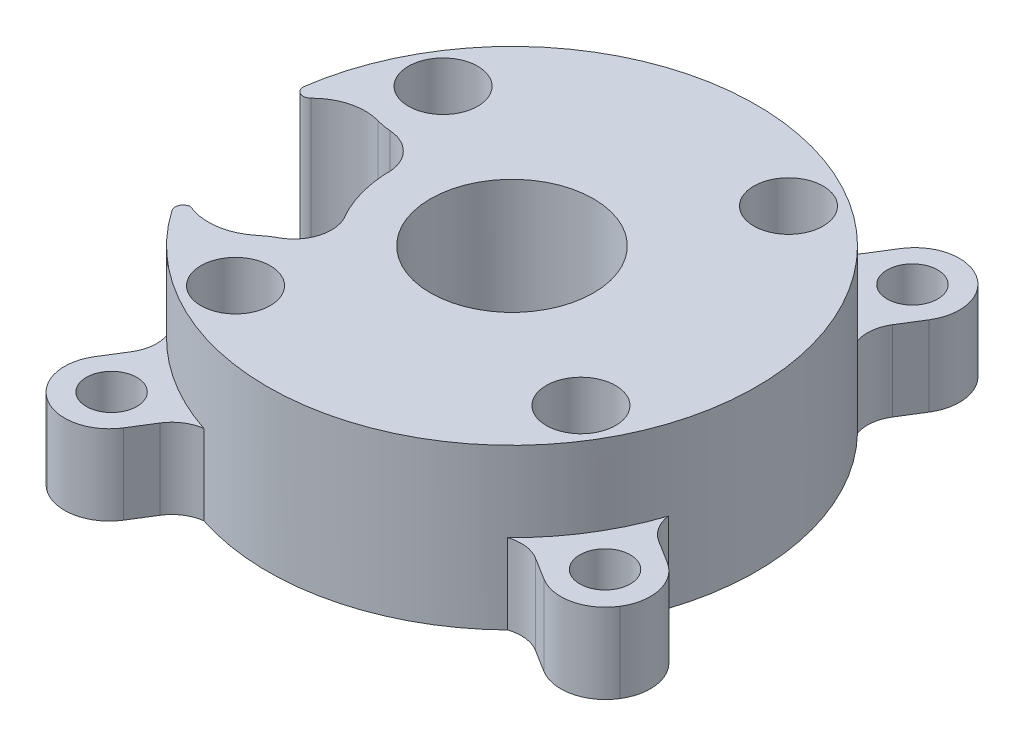
SolidWorks part; units mm, degrees
ref_plane "Front Plane" through (0, 0, 0) normal (0, 0, 1) x (1, 0, 0)
ref_plane "Top Plane" through (0, 0, 0) normal (0, 1, 0) x (1, 0, 0)
ref_plane "Right Plane" through (0, 0, 0) normal (1, 0, 0) x (0, 0, -1)
sketch "Sketch1" plane through (0, 0, 0) normal (0, 1, 0) x (1, 0, 0)
  line L0 (-7.8696, -16.5329) -> (-4.3445, -17.9784) construction
  line L2 (-5.1285, -8.2334) -> (-7.1429, -11.4673) construction
  line L3 (-5.1285, -8.2334) -> (0, 0) construction
  line L4 (-4.4173, -15.8896) -> (-5.3876, -15.4917)
  line L5 (-6.8331, -19.0168) -> (-5.8628, -19.4147)
  line L6 (-10.7934, 4.6284) -> (-9.9033, 4.0739)
  line L22 (-8.9133, 7.6467) -> (-8.0232, 7.0923)
  line L25 (-4.6284, -10.7934) -> (-4.0739, -9.9033)
  line L26 (-7.6467, -8.9133) -> (-7.0923, -8.0232)
  line L33 (-8.2334, 5.1285) -> (-11.4673, 7.1429) construction
  line L34 (4.6284, 10.7934) -> (4.0739, 9.9033)
  line L35 (7.6467, 8.9133) -> (7.0923, 8.0232)
  line L36 (5.1285, 8.2334) -> (7.1429, 11.4673) construction
  line L37 (10.7934, -4.6284) -> (9.9033, -4.0739)
  line L38 (8.9133, -7.6467) -> (8.0232, -7.0923)
  line L39 (8.2334, -5.1285) -> (11.4673, -7.1429) construction
  arc A2 (-3.014, -9.2199) -> (-6.9463, -6.7705) centre (0, 0) ccw
  arc A3 (-9.9033, 4.0739) -> (-9.2199, 3.014) centre (-10.6843, 2.8201) cw
  arc A4 (-11.3595, 7.0757) -> (-10.7934, 4.6284) centre (-9.8553, 6.1345) ccw
  arc A6 (-11.3595, 7.0757) -> (-8.9133, 7.6467) centre (-9.8515, 6.1406) cw
  arc A42 (-4.4173, -15.8896) -> (-2.8621, -15.4979) centre (-3.905, -14.6404) ccw
  arc A43 (-5.3876, -15.4917) -> (-7.8696, -16.5329) centre (-6.109, -17.251) ccw
  arc A45 (-7.8696, -16.5329) -> (-6.8331, -19.0168) centre (-6.1117, -17.2576) ccw
  arc A46 (-5.0304, -20.7855) -> (-5.8628, -19.4147) centre (-6.375, -20.664) ccw
  arc A47 (-2.8621, -15.4979) -> (-5.0304, -20.7855) centre (4.6303, -21.6586) ccw
  arc A48 (-8.0232, 7.0923) -> (-6.7705, 6.9463) centre (-7.2422, 8.3461) ccw
  arc A49 (-4.0739, -9.9033) -> (-3.014, -9.2199) centre (-2.8201, -10.6843) cw
  arc A50 (-7.0757, -11.3595) -> (-4.6284, -10.7934) centre (-6.1345, -9.8553) ccw
  arc A51 (-7.0757, -11.3595) -> (-7.6467, -8.9133) centre (-6.1406, -9.8515) cw
  arc A52 (-7.0923, -8.0232) -> (-6.9463, -6.7705) centre (-8.3461, -7.2422) ccw
  arc A53 (4.0739, 9.9033) -> (3.014, 9.2199) centre (2.8201, 10.6843) cw
  arc A54 (7.0757, 11.3595) -> (4.6284, 10.7934) centre (6.1345, 9.8553) ccw
  arc A55 (7.0757, 11.3595) -> (7.6467, 8.9133) centre (6.1406, 9.8515) cw
  arc A56 (7.0923, 8.0232) -> (6.9463, 6.7705) centre (8.3461, 7.2422) ccw
  arc A57 (9.9033, -4.0739) -> (9.2199, -3.014) centre (10.6843, -2.8201) cw
  arc A58 (11.3595, -7.0757) -> (10.7934, -4.6284) centre (9.8553, -6.1345) ccw
  arc A59 (11.3595, -7.0757) -> (8.9133, -7.6467) centre (9.8515, -6.1406) cw
  arc A60 (8.0232, -7.0923) -> (6.7705, -6.9463) centre (7.2422, -8.3461) ccw
  point P42 (-13.0295, 5.5229)
  point P43 (-11.993, 3.0389)
  point P44 (-11.2689, 4.8048)
  point P45 (-11.2716, 4.7982)
  point P46 (-11.0227, 2.6411)
  point P47 (-10.5475, 6.5641)
  point P48 (-11.5349, 1.3918)
  point P49 (-10.1902, 1.2703)
  point P53 (-2.4431, -9.256)
  point P56 (-10.2156, 2.0562)
  point P57 (-0.5296, 0.3972)
  point P58 (-8.5918, 6.0161)
  point P64 (-7.2304, -6.274)
  point P102 (0, 0)
  dimension "D9" = 1.9014
  dimension "D11" = 1.3502
  dimension "D13" = 1.905
  dimension "D3" = 3.81
  dimension "D10" = 1.0487
extrude "Boss-Extrude2" add sketch "Sketch1" along normal blind 3.175 contours A48 L22 A6 A4 L6 A3 A2 | A52 L26 A51 A50 L25 A49 A2 | A56 L35 A55 A54 L34 A53 A2 | A60 L38 A59 A58 L37 A57 A2
sketch "Sketch3" plane through (0, 3.175, 0) normal (0, 1, 0) x (1, 0, 0)
  circle A0 centre (0, 0) radius 9.7
extrude "Boss-Extrude4" add sketch "Sketch3" along normal blind 3.175
sketch "Sketch4" plane through (0, 3.175, 0) normal (0, 1, 0) x (1, 0, 0)
  line L0 (-7.0757, -11.3595) -> (-5.1285, -8.2334) construction
  arc A0 (-6.9463, -6.7705) -> (-3.014, -9.2199) centre (0, 0) ccw construction
  circle A1 centre (-6.1021, -9.7965) radius 1.0033
  circle A2 centre (-9.7965, 6.1021) radius 1.0033
  circle A3 centre (6.1021, 9.7965) radius 1.0033
  circle A4 centre (9.7965, -6.1021) radius 1.0033
  dimension "D1" = 2.0066
  dimension "D3" = 9.7965
  dimension "D4" = 11.5415
  dimension "D2" = 4
extrude "Cut-Extrude1" cut sketch "Sketch4" against normal blind 3.175
sketch "Sketch6" plane through (0, 0, 0) normal (0, -1, 0) x (1, 0, 0)
  line L0 (-8.6009, 2.0015) -> (-4.7665, 1.2946) construction
  circle A0 centre (0, 0) radius 9.7 construction
  circle A1 centre (-4.1203, 6.8573) radius 1.25
  arc A2 (-7.7408, 4.1889) -> (-8.8653, -0.334) centre (0.1332, -0.17) ccw
  arc A3 (-8.8653, -0.334) -> (-6.9609, -1.6427) centre (-7.3713, -0.1999) ccw
  arc A4 (-6.3873, -1.5416) -> (-4.9858, 0.0725) centre (-6.4812, -0.0445) ccw
  arc A5 (-5.4387, 4.7136) -> (-7.7408, 4.1889) centre (-6.3841, 3.5491) ccw
  arc A6 (-4.2583, 2.4276) -> (-4.9451, 4.3741) centre (-5.6282, 3.0387) ccw
  arc A7 (-4.2583, 2.4276) -> (-4.9858, 0.0725) centre (0.1064, -0.2106) ccw
  circle A8 centre (6.8573, 4.1203) radius 1.25
  circle A9 centre (4.1203, -6.8573) radius 1.25
  circle A10 centre (-6.8573, -4.1203) radius 1.25
  parabola Q0 (-6.9609, -1.6427) -> (-6.3873, -1.5416) focus (-6.003, -2.6403) apex (-5.7771, -1.5853)
  spline S0 degree 2 poles (-4.9451, 4.3741) (-5.0821, 4.4442) (-5.2471, 4.5653) (-5.34, 4.6335) (-5.4387, 4.7136) knots 0 0 0 0.6 0.6 1 1 1
  point P29 (0, 0)
  dimension "D2" = 1.5
extrude "Cut-Extrude2" cut sketch "Sketch6" against normal through all
sketch "Sketch7" plane through (0, 0, 0) normal (0, -1, 0) x (1, 0, 0)
  arc A0 (-6.9463, 6.7705) -> (-9.2199, -3.014) centre (0, 0) ccw construction
  arc A2 (-6.9609, -1.6427) -> (-9.6852, 0.5356) centre (-7.5467, 0.4174) cw
  arc A4 (-5.4387, 4.7136) -> (-8.8941, 3.871) centre (-6.8464, 2.9798) ccw
  arc A6 (-6.9463, 6.7705) -> (-9.2199, -3.014) centre (0, 0) ccw
  arc A7 (-8.8941, 3.871) -> (-9.6852, 0.5356) centre (0, 0) ccw
  arc A16 (-8.8653, -0.334) -> (-6.9609, -1.6427) centre (-7.3713, -0.1999) ccw
  arc A17 (-7.7408, 4.1889) -> (-8.8653, -0.334) centre (0.1332, -0.17) ccw
  arc A18 (-5.4387, 4.7136) -> (-7.7408, 4.1889) centre (-6.3841, 3.5491) ccw
  arc A19 (-8.8653, -0.334) -> (-6.9609, -1.6427) centre (-7.3713, -0.1999) ccw
  arc A20 (-7.7408, 4.1889) -> (-8.8653, -0.334) centre (0.1332, -0.17) ccw
  arc A21 (-5.4387, 4.7136) -> (-7.7408, 4.1889) centre (-6.3841, 3.5491) ccw
  parabola Q23 (-6.9609, -1.6427) -> (-6.3873, -1.5416) focus (-6.003, -2.6403) apex (-5.7771, -1.5853) construction
  spline S0 degree 2 poles (-4.9451, 4.3741) (-5.0821, 4.4442) (-5.2471, 4.5653) (-5.34, 4.6335) (-5.4387, 4.7136) knots 0 0 0 0.6 0.6 1 1 1 construction
  dimension "D1" = 0
  dimension "D2" = 0
extrude "Cut-Extrude3" cut sketch "Sketch7" against normal through all
sketch "Sketch8" plane through (0, 0, 0) normal (0, -1, 0) x (1, 0, 0)
  line L0 (0, 0) -> (-4.7665, 1.2946) construction
  line L1 (-9.6043, -1.3592) -> (-10.3645, 0.8697)
  line L2 (-10.3645, 0.8697) -> (-8.848, 0.8697)
  line L3 (-8.848, 0.8697) -> (-9.0664, -1.0918)
  line L4 (-8.8941, 3.871) -> (-9.6852, 0.5356) construction
  line L5 (-9.2897, 2.2033) -> (0, 0) construction
  line L6 (-8.2961, 3.1965) -> (-7.6103, 5.0472)
  line L7 (-9.6511, 3.8776) -> (-8.2961, 3.1965)
  line L8 (-7.9709, 5.5277) -> (-9.6511, 3.8776)
  arc A0 (-9.6043, -1.3592) -> (-9.0664, -1.0918) centre (-9.291, -1.3148) cw
  arc A1 (-9.6852, 0.5356) -> (-9.2199, -3.014) centre (0, 0) ccw construction
  arc A2 (-9.6852, 0.5356) -> (-6.9613, -1.6428) centre (-7.5467, 0.4174) ccw construction
  arc A3 (-4.2583, 2.4276) -> (-4.9858, 0.0725) centre (0.1064, -0.2106) ccw construction
  arc A4 (-7.9709, 5.5277) -> (-7.6103, 5.0472) centre (-7.7108, 5.3473) ccw
extrude "Cut-Extrude4" cut sketch "Sketch8" against normal through all
sketch "Sketch9" plane through (0, 0, 0) normal (0, -1, 0) x (1, 0, 0)
  circle A0 centre (0, 0) radius 3.2385
  dimension "D1" = 6.477
extrude "Cut-Extrude5" cut sketch "Sketch9" against normal through all
sketch "Sketch11" plane through (0, 6.35, 0) normal (0, 1, 0) x (1, 0, 0)
  circle A0 centre (4.1203, 6.8573) radius 1.25 construction
  circle A1 centre (6.8573, -4.1203) radius 1.25 construction
  circle A2 centre (-4.1203, -6.8573) radius 1.25 construction
  circle A3 centre (-6.8573, 4.1203) radius 1.25 construction
  circle A4 centre (4.1203, 6.8573) radius 1.25 construction
  circle A5 centre (6.8573, -4.1203) radius 1.25 construction
  circle A6 centre (-4.1203, -6.8573) radius 1.25 construction
  circle A7 centre (-6.8573, 4.1203) radius 1.25 construction
  circle A8 centre (-6.8573, 4.1203) radius 1.377
  circle A9 centre (4.1203, 6.8573) radius 1.377
  circle A10 centre (6.8573, -4.1203) radius 1.377
  circle A11 centre (-4.1203, -6.8573) radius 1.377
  arc A12 (-7.7287, -5.0314) -> (-7.9709, -5.5277) centre (-7.7108, -5.3473) ccw construction
  arc A13 (-7.7287, -5.0314) -> (-5.4387, -4.7136) centre (-6.8464, -2.9798) ccw construction
  arc A14 (-4.9451, -4.3741) -> (-4.2583, -2.4276) centre (-5.6282, -3.0387) ccw construction
  arc A15 (-4.9858, -0.0725) -> (-4.2583, -2.4276) centre (0.1064, 0.2106) ccw construction
  arc A16 (-9.6043, 1.3592) -> (-9.0664, 1.0918) centre (-9.291, 1.3148) ccw construction
  arc A17 (-6.9613, 1.6428) -> (-9.0664, 1.0918) centre (-7.5467, -0.4174) ccw construction
  arc A18 (-4.9858, -0.0725) -> (-6.3873, 1.5416) centre (-6.4812, 0.0445) ccw construction
  arc A19 (-7.7287, -5.0314) -> (-7.9709, -5.5277) centre (-7.7108, -5.3473) ccw construction
  arc A20 (-7.7287, -5.0314) -> (-5.4387, -4.7136) centre (-6.8464, -2.9798) ccw construction
  arc A21 (-4.9451, -4.3741) -> (-4.2583, -2.4276) centre (-5.6282, -3.0387) ccw construction
  arc A22 (-4.9858, -0.0725) -> (-4.2583, -2.4276) centre (0.1064, 0.2106) ccw construction
  arc A23 (-9.6043, 1.3592) -> (-9.0664, 1.0918) centre (-9.291, 1.3148) ccw construction
  arc A24 (-6.9613, 1.6428) -> (-9.0664, 1.0918) centre (-7.5467, -0.4174) ccw construction
  arc A25 (-4.9858, -0.0725) -> (-6.3873, 1.5416) centre (-6.4812, 0.0445) ccw construction
  parabola Q0 (-6.9609, 1.6427) -> (-6.3873, 1.5416) focus (-6.003, 2.6403) apex (-5.7771, 1.5853) construction
  parabola Q1 (-6.9609, 1.6427) -> (-6.3873, 1.5416) focus (-6.003, 2.6403) apex (-5.7771, 1.5853) construction
  spline S0 degree 2 poles (-1414.679, -2652.3554) (32.7402, 23.3103) (-5.2471, -4.5653) (-48.5341, -36.3298) (-1365.8772, -2678.3133) knots -137.508267 -137.508267 -137.508267 0.6 0.6 187.104381 187.104381 187.104381 only from (-4.9451, -4.3741) to (-5.4387, -4.7136) construction
  spline S1 degree 2 poles (-4.9451, -4.3741) (-5.0821, -4.4442) (-5.2471, -4.5653) (-5.34, -4.6335) (-5.4387, -4.7136) knots 0 0 0 0.6 0.6 1 1 1 construction
  dimension "D1" = 0.127
extrude "Cut-Extrude7" cut sketch "Sketch11" against normal through all
sketch "Sketch12" plane through (0, 0, 0) normal (0, -1, 0) x (1, 0, 0)
  line L9 (-9.9033, -4.0739) -> (-10.7934, -4.6284)
  line L10 (-8.9133, -7.6467) -> (-8.0232, -7.0923)
  line L11 (4.0739, -9.9033) -> (4.6284, -10.7934)
  line L12 (7.6467, -8.9133) -> (7.0923, -8.0232)
  line L13 (9.9033, 4.0739) -> (10.7934, 4.6284)
  line L14 (8.9133, 7.6467) -> (8.0232, 7.0923)
  line L15 (-4.0739, 9.9033) -> (-4.6284, 10.7934)
  line L16 (-7.6467, 8.9133) -> (-7.0923, 8.0232)
  line L17 (-6.9606, -1.6426) -> (-6.9611, -1.6427)
  line L18 (-9.9033, -4.0739) -> (-10.7934, -4.6284)
  line L19 (-8.9133, -7.6467) -> (-8.0232, -7.0923)
  line L20 (4.0739, -9.9033) -> (4.6284, -10.7934)
  line L21 (7.6467, -8.9133) -> (7.0923, -8.0232)
  line L22 (9.9033, 4.0739) -> (10.7934, 4.6284)
  line L23 (8.9133, 7.6467) -> (8.0232, 7.0923)
  line L24 (-4.0739, 9.9033) -> (-4.6284, 10.7934)
  line L25 (-7.6467, 8.9133) -> (-7.0923, 8.0232)
  arc A0 (-6.9463, 6.7705) -> (-9.2199, -3.014) centre (0, 0) ccw
  arc A1 (6.7705, 6.9463) -> (-3.014, 9.2199) centre (0, 0) ccw
  arc A2 (6.9463, -6.7705) -> (9.2199, 3.014) centre (0, 0) ccw
  arc A3 (-6.7705, -6.9463) -> (3.014, -9.2199) centre (0, 0) ccw
  circle A4 centre (9.7965, 6.1021) radius 1.0033 construction
  circle A5 centre (6.1021, -9.7965) radius 1.0033 construction
  circle A6 centre (-9.7965, -6.1021) radius 1.0033 construction
  circle A7 centre (-6.1021, 9.7965) radius 1.0033 construction
  circle A8 centre (9.7965, 6.1021) radius 1.0033
  circle A9 centre (6.1021, -9.7965) radius 1.0033
  circle A10 centre (-9.7965, -6.1021) radius 1.0033
  circle A11 centre (-6.1021, 9.7965) radius 1.0033
  arc A28 (-9.0664, -1.0918) -> (-6.9611, -1.6427) centre (-7.5467, 0.4174) ccw
  arc A29 (-9.0664, -1.0918) -> (-9.6043, -1.3592) centre (-9.291, -1.3148) ccw
  arc A30 (-9.6043, -1.3592) -> (-9.2199, -3.014) centre (0, 0) ccw
  arc A31 (-9.9033, -4.0739) -> (-9.2199, -3.014) centre (-10.6843, -2.8201) ccw
  arc A32 (-10.7934, -4.6284) -> (-11.3595, -7.0757) centre (-9.8553, -6.1345) ccw
  arc A33 (-11.3595, -7.0757) -> (-8.9133, -7.6467) centre (-9.8515, -6.1406) ccw
  arc A34 (-6.7705, -6.9463) -> (-8.0232, -7.0923) centre (-7.2422, -8.3461) ccw
  arc A35 (-6.7705, -6.9463) -> (3.014, -9.2199) centre (0, 0) ccw
  arc A36 (4.0739, -9.9033) -> (3.014, -9.2199) centre (2.8201, -10.6843) ccw
  arc A37 (4.6284, -10.7934) -> (7.0757, -11.3595) centre (6.1345, -9.8553) ccw
  arc A38 (7.0757, -11.3595) -> (7.6467, -8.9133) centre (6.1406, -9.8515) ccw
  arc A39 (6.9463, -6.7705) -> (7.0923, -8.0232) centre (8.3461, -7.2422) ccw
  arc A40 (6.9463, -6.7705) -> (9.2199, 3.014) centre (0, 0) ccw
  arc A41 (9.9033, 4.0739) -> (9.2199, 3.014) centre (10.6843, 2.8201) ccw
  arc A42 (10.7934, 4.6284) -> (11.3595, 7.0757) centre (9.8553, 6.1345) ccw
  arc A43 (11.3595, 7.0757) -> (8.9133, 7.6467) centre (9.8515, 6.1406) ccw
  arc A44 (6.7705, 6.9463) -> (8.0232, 7.0923) centre (7.2422, 8.3461) ccw
  arc A45 (6.7705, 6.9463) -> (-3.014, 9.2199) centre (0, 0) ccw
  arc A46 (-4.0739, 9.9033) -> (-3.014, 9.2199) centre (-2.8201, 10.6843) ccw
  arc A47 (-4.6284, 10.7934) -> (-7.0757, 11.3595) centre (-6.1345, 9.8553) ccw
  arc A48 (-7.0757, 11.3595) -> (-7.6467, 8.9133) centre (-6.1406, 9.8515) ccw
  arc A49 (-6.9463, 6.7705) -> (-7.0923, 8.0232) centre (-8.3461, 7.2422) ccw
  arc A50 (-6.9463, 6.7705) -> (-7.9709, 5.5277) centre (0, 0) ccw
  arc A51 (-7.9709, 5.5277) -> (-7.7287, 5.0314) centre (-7.7108, 5.3473) ccw
  arc A52 (-5.4387, 4.7136) -> (-7.7287, 5.0314) centre (-6.8464, 2.9798) ccw
  arc A53 (-4.2583, 2.4276) -> (-4.9451, 4.3741) centre (-5.6282, 3.0387) ccw
  arc A54 (-4.2583, 2.4276) -> (-4.9858, 0.0725) centre (0.1064, -0.2106) ccw
  arc A55 (-6.3873, -1.5416) -> (-4.9858, 0.0725) centre (-6.4812, -0.0445) ccw
  arc A59 (-9.9033, -4.0739) -> (-9.2199, -3.014) centre (-10.6843, -2.8201) ccw
  arc A60 (-10.7934, -4.6284) -> (-11.3595, -7.0757) centre (-9.8553, -6.1345) ccw
  arc A61 (-11.3595, -7.0757) -> (-8.9133, -7.6467) centre (-9.8515, -6.1406) ccw
  arc A62 (-6.7705, -6.9463) -> (-8.0232, -7.0923) centre (-7.2422, -8.3461) ccw
  arc A63 (-6.7705, -6.9463) -> (3.014, -9.2199) centre (0, 0) ccw
  arc A64 (4.0739, -9.9033) -> (3.014, -9.2199) centre (2.8201, -10.6843) ccw
  arc A65 (4.6284, -10.7934) -> (7.0757, -11.3595) centre (6.1345, -9.8553) ccw
  arc A66 (7.0757, -11.3595) -> (7.6467, -8.9133) centre (6.1406, -9.8515) ccw
  arc A67 (6.9463, -6.7705) -> (7.0923, -8.0232) centre (8.3461, -7.2422) ccw
  arc A68 (6.9463, -6.7705) -> (9.2199, 3.014) centre (0, 0) ccw
  arc A69 (9.9033, 4.0739) -> (9.2199, 3.014) centre (10.6843, 2.8201) ccw
  arc A70 (10.7934, 4.6284) -> (11.3595, 7.0757) centre (9.8553, 6.1345) ccw
  arc A71 (11.3595, 7.0757) -> (8.9133, 7.6467) centre (9.8515, 6.1406) ccw
  arc A72 (6.7705, 6.9463) -> (8.0232, 7.0923) centre (7.2422, 8.3461) ccw
  arc A73 (6.7705, 6.9463) -> (-3.014, 9.2199) centre (0, 0) ccw
  arc A74 (-4.0739, 9.9033) -> (-3.014, 9.2199) centre (-2.8201, 10.6843) ccw
  arc A75 (-4.6284, 10.7934) -> (-7.0757, 11.3595) centre (-6.1345, 9.8553) ccw
  arc A76 (-7.0757, 11.3595) -> (-7.6467, 8.9133) centre (-6.1406, 9.8515) ccw
  arc A77 (-6.9463, 6.7705) -> (-7.0923, 8.0232) centre (-8.3461, 7.2422) ccw
  parabola Q1 (-6.3873, -1.5416) -> (-6.9606, -1.6426) focus (-6.003, -2.6403) apex (-5.7771, -1.5853)
  spline S1 degree 2 poles (-469.4096, 890.564) (-29.9453, 22.6891) (-5.2471, 4.5653) (16.9078, -11.6922) (-466.1891, 891.6429) knots -106.013424 -106.013424 -106.013424 0.4 0.4 80.947287 80.947287 80.947287 only from (-5.4387, 4.7136) to (-4.9451, 4.3741)
  dimension "D1" = 0
